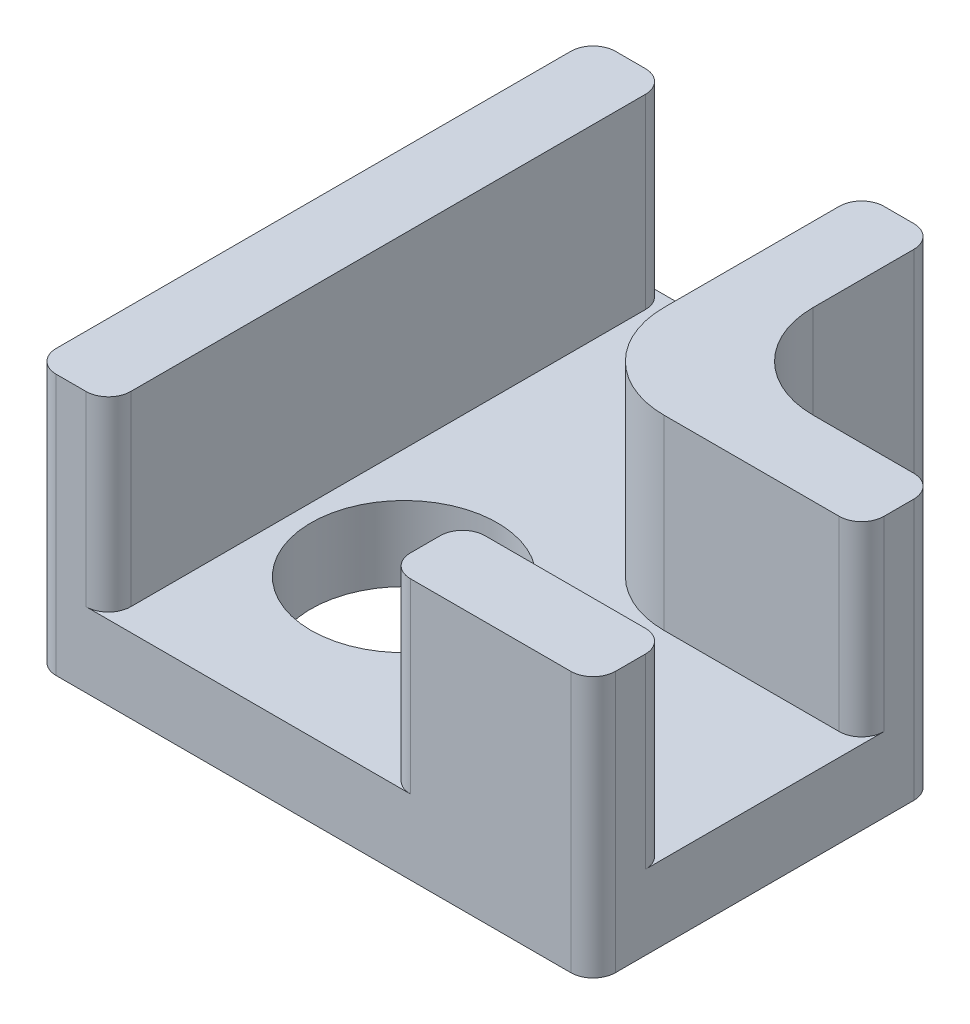
SolidWorks part; units mm, degrees
ref_plane "Front Plane" through (0, 0, 0) normal (0, 0, 1) x (1, 0, 0)
ref_plane "Top Plane" through (0, 0, 0) normal (0, 1, 0) x (1, 0, 0)
ref_plane "Right Plane" through (0, 0, 0) normal (1, 0, 0) x (0, 0, -1)
sketch "Sketch1" plane through (0, 0, 0) normal (0, 1, 0) x (1, 0, 0)
  line L0 (0, 0) -> (30, 0)
  line L1 (30, 0) -> (30, 18.4)
  line L2 (30, 18.4) -> (18.4, 18.4)
  line L3 (18.4, 18.4) -> (18.4, 30)
  line L4 (18.4, 30) -> (0, 30)
  line L5 (0, 30) -> (0, 0)
  dimension "D1" = 18.4
  dimension "D2" = 30
extrude "Boss-Extrude1" add sketch "Sketch1" along normal blind 30.9
shell "Shell1" thickness 4
sketch "Sketch2" plane through (0, 0, 0) normal (0, 0, 1) x (1, 0, 0)
  line L0 (0, 30.9) -> (0, 0) construction
  line L1 (4, 26.9) -> (19, 26.9)
  line L2 (4, 26.9) -> (4, 4)
  line L3 (4, 4) -> (19, 4)
  line L4 (19, 26.9) -> (19, 4)
  line L5 (0, 30.9) -> (30, 30.9) construction
  line L6 (0, 0) -> (30, 0) construction
  dimension "D1" = 4
  dimension "D2" = 4
  dimension "D3" = 4
  dimension "D4" = 15
extrude "Cut-Extrude1" cut sketch "Sketch2" against normal up to next
sketch "Sketch3" plane through (0, 30.9, 0) normal (0, 1, 0) x (1, 0, 0)
  line L6 (0, 30) -> (0, 0)
  line L7 (0, 0) -> (30, 0)
  line L8 (30, 0) -> (30, 18.4)
  line L9 (30, 18.4) -> (18.4, 18.4)
  line L10 (18.4, 18.4) -> (18.4, 30)
  line L11 (18.4, 30) -> (0, 30)
  line L12 (0, 30) -> (0, 0)
  line L13 (0, 0) -> (30, 0)
  line L14 (30, 0) -> (30, 18.4)
  line L15 (30, 18.4) -> (18.4, 18.4)
  line L16 (18.4, 18.4) -> (18.4, 30)
  line L17 (18.4, 30) -> (0, 30)
  dimension "D1" = 0
extrude "Cut-Extrude2" cut sketch "Sketch3" against normal offset from surface (16.9 mm away) 10 up to face at (16.85, 4, -12.1)
fillet "Fillet1" radius 5 2 edges at (18.4, 7, -18.4) (14.4, 9, -14.4)
fillet "Fillet2" radius 1.2 12 edges at (0, 7, 0) (0, 7, -30) (18.4, 7, -30) (30, 7, -18.4) (30, 7, 0) (30, 9, -14.4) (30, 9, -4) (19, 9, -4) (19, 9, 0) (4, 9, -30) (14.4, 9, -30) (4, 9, 0)
sketch "Sketch4" plane through (0, 4, 0) normal (0, 1, 0) x (1, 0, 0)
  line L1 (0, 0) -> (19.8645, 0) construction
  line L2 (0, 0) -> (0, 19.8645) construction
  line L3 (0, 19.8645) -> (19.8645, 19.8645) construction
  line L4 (19.8645, 0) -> (19.8645, 19.8645) construction
  line L5 (0, 0) -> (19.8645, 19.8645) construction
  line L6 (0, 19.8645) -> (19.8645, 0) construction
  arc A0 (18.4, 23.4) -> (23.4, 18.4) centre (23.4, 23.4) ccw construction
  circle A1 centre (9.9322, 9.9322) radius 5
  point P4 (9.9322, 9.9322)
  dimension "D1" = 10
extrude "Cut-Extrude5" cut sketch "Sketch4" against normal through all
equation "\"D1@Sketch1\"=10.4mm+2*\"thick\""
equation "\"thick\"= 4mm"
equation "\"D1@Shell1\"=\"thick\""
equation "\"D2@Sketch2\"=\"thick\""
equation "\"D1@Sketch2\"=\"thick\""
equation "\"D3@Sketch2\"=\"thick\""
